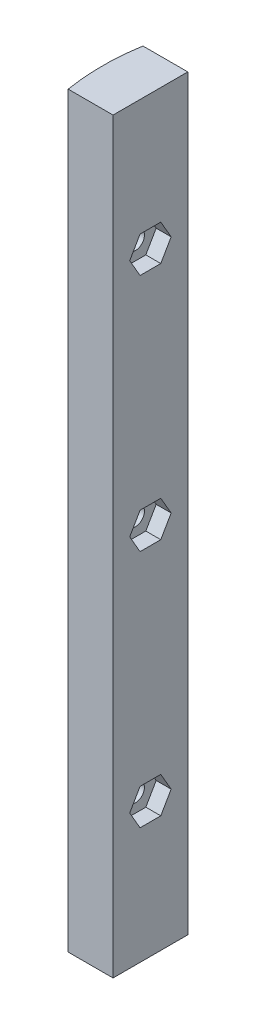
SolidWorks part; units mm, degrees
material "ABS"
ref_plane "Front Plane" through (0, 0, 0) normal (0, 0, 1) x (1, 0, 0)
ref_plane "Top Plane" through (0, 0, 0) normal (0, 1, 0) x (1, 0, 0)
ref_plane "Right Plane" through (0, 0, 0) normal (1, 0, 0) x (0, 0, -1)
sketch "Sketch1" plane through (0, 0, 0) normal (0, 1, 0) x (1, 0, 0)
  line L0 (-65.5047, 11.4784) -> (-65.5047, -13.5216)
  line L1 (-65.5047, 11.4784) -> (-75.5047, 11.4784)
  line L2 (-65.5047, -13.5216) -> (-75.5047, -13.5216)
  arc A0 (-75.5047, 11.4784) -> (-75.5047, -13.5216) centre (-0.337, -1.0216) ccw
  point P3 (-65.5047, -1.0216)
  dimension "D1" = 25
  dimension "D3" = 152.4
  dimension "D2" = 10
extrude "Boss-Extrude1" add sketch "Sketch1" along normal blind 25
sketch "Sketch2" plane through (-65.5047, 0, 0) normal (1, 0, 0) x (0, 0, -1)
  line L0 (-13.5216, 25) -> (-13.5216, 0) construction
  line L1 (-13.5216, 25) -> (11.4784, 25) construction
  circle A0 centre (-1.0216, 12.5) radius 3
  dimension "D1" = 6
  dimension "D2" = 12.5
  dimension "D3" = 12.5
extrude "Cut-Extrude1" cut sketch "Sketch2" against normal blind 25
sketch "Sketch3" plane through (-65.5047, 0, 0) normal (1, 0, 0) x (0, 0, -1)
  line L0 (11.4784, 25) -> (11.4784, 0) construction
  line L1 (-13.5216, 0) -> (11.4784, 0) construction
  line L2 (-13.5216, 25) -> (-13.5216, 0) construction
  line L3 (-13.5216, 25) -> (11.4784, 25) construction
  line L4 (11.4784, 25) -> (11.4784, 0)
  line L5 (-13.5216, 0) -> (11.4784, 0)
  line L6 (-13.5216, 25) -> (-13.5216, 0)
  line L7 (-13.5216, 25) -> (11.4784, 25)
  line L9 (5.9066, 12.5) -> (2.4425, 18.5)
  line L10 (2.4425, 18.5) -> (-4.4857, 18.5)
  line L11 (-4.4857, 18.5) -> (-7.9498, 12.5)
  line L12 (-7.9498, 12.5) -> (-4.4857, 6.5)
  line L13 (-4.4857, 6.5) -> (2.4425, 6.5)
  line L14 (2.4425, 6.5) -> (5.9066, 12.5)
  circle A0 centre (-1.0216, 12.5) radius 3 construction
  circle A1 centre (-1.0216, 12.5) radius 3 construction
  circle A2 centre (-1.0216, 12.5) radius 6 construction
  dimension "D1" = 12
extrude "Boss-Extrude2" add sketch "Sketch3" along normal blind 5
sketch "Sketch4" plane through (0, 25, 0) normal (0, 1, 0) x (1, 0, 0)
  line L0 (-75.5047, -13.5216) -> (-60.5047, -13.5216) construction
  line L1 (-60.5047, 11.4784) -> (-60.5047, -13.5216) construction
  line L2 (-60.5047, 11.4784) -> (-75.5047, 11.4784) construction
  line L3 (-75.5047, -13.5216) -> (-60.5047, -13.5216)
  line L4 (-60.5047, 11.4784) -> (-60.5047, -13.5216)
  line L5 (-60.5047, 11.4784) -> (-75.5047, 11.4784)
  arc A0 (-75.5047, 11.4784) -> (-75.5047, -13.5216) centre (-0.337, -1.0216) ccw construction
  arc A1 (-75.5047, 11.4784) -> (-75.5047, -13.5216) centre (-0.337, -1.0216) ccw
extrude "Boss-Extrude3" add sketch "Sketch4" along normal blind 192.5
sketch "Sketch5" plane through (0, 0, 0) normal (0, -1, 0) x (1, 0, 0)
  line L0 (-75.5047, 13.5216) -> (-60.5047, 13.5216) construction
  line L1 (-60.5047, 13.5216) -> (-60.5047, -11.4784) construction
  line L2 (-60.5047, -11.4784) -> (-75.5047, -11.4784) construction
  line L3 (-75.5047, 13.5216) -> (-60.5047, 13.5216)
  line L4 (-60.5047, 13.5216) -> (-60.5047, -11.4784)
  line L5 (-60.5047, -11.4784) -> (-75.5047, -11.4784)
  arc A0 (-75.5047, 13.5216) -> (-75.5047, -11.4784) centre (-0.337, 1.0216) ccw construction
  arc A1 (-75.5047, 13.5216) -> (-75.5047, -11.4784) centre (-0.337, 1.0216) ccw
extrude "Boss-Extrude4" add sketch "Sketch5" along normal blind 32.5
pattern_linear "LPattern4" count 3 spacing 80 along (0, 1, 0) of "Cut-Extrude1"
sketch "Sketch6" plane through (-60.5047, 0, 0) normal (1, 0, 0) x (0, 0, -1)
  line L14 (5.9066, 92.5) -> (2.4425, 98.5)
  line L16 (2.4425, 98.5) -> (-4.4857, 98.5)
  line L17 (-4.4857, 98.5) -> (-7.9498, 92.5)
  line L18 (-7.9498, 92.5) -> (-4.4857, 86.5)
  line L19 (-4.4857, 86.5) -> (2.4425, 86.5)
  line L20 (2.4425, 86.5) -> (5.9066, 92.5)
  line L21 (5.9066, 172.5) -> (2.4425, 178.5)
  line L22 (2.4425, 178.5) -> (-4.4857, 178.5)
  line L23 (-4.4857, 178.5) -> (-7.9498, 172.5)
  line L24 (-7.9498, 172.5) -> (-4.4857, 166.5)
  line L25 (-4.4857, 166.5) -> (2.4425, 166.5)
  line L26 (2.4425, 166.5) -> (5.9066, 172.5)
  circle A0 centre (-1.0216, 92.5) radius 6 construction
  circle A1 centre (-1.0216, 172.5) radius 6 construction
  point P0 (-1.0216, 12.5)
  point P1 (-1.0216, 92.5)
  point P3 (-1.0216, 172.5)
  point P4 (69.5343, 92.5)
  point P14 (-1.0216, 166.5)
  point P22 (-1.0216, 86.5)
  dimension "D1" = 12
  dimension "D2" = 12
extrude "Cut-Extrude2" cut sketch "Sketch6" against normal blind 5
